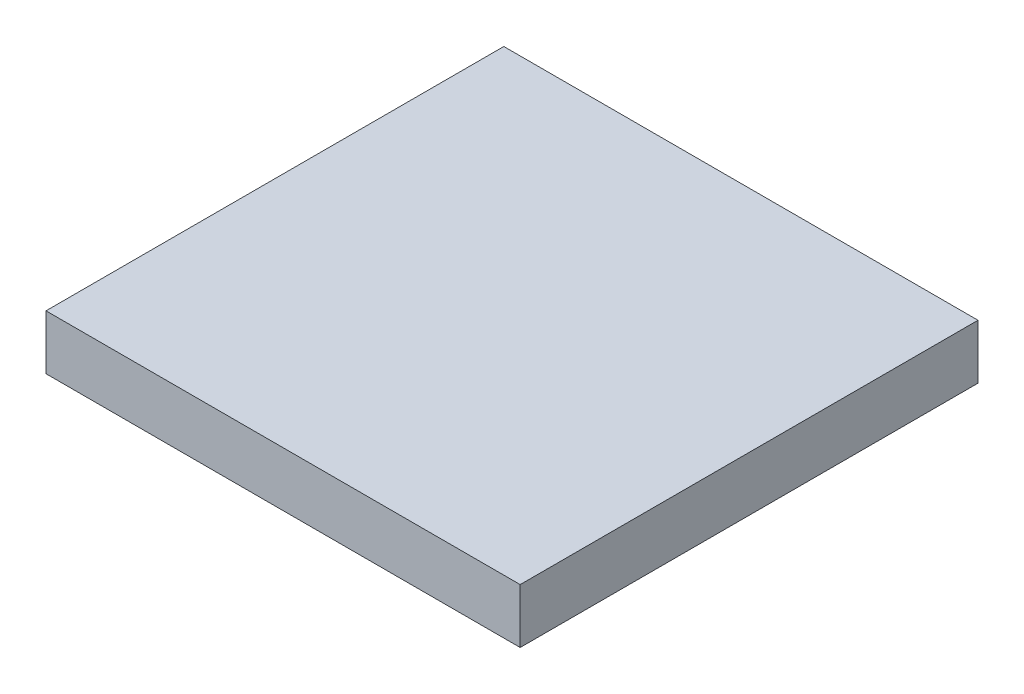
SolidWorks part; units mm, degrees
ref_plane "Front Plane" through (0, 0, 0) normal (0, 0, 1) x (1, 0, 0)
ref_plane "Top Plane" through (0, 0, 0) normal (0, 1, 0) x (1, 0, 0)
ref_plane "Right Plane" through (0, 0, 0) normal (1, 0, 0) x (0, 0, -1)
sketch "Sketch1" plane through (0, 0, 0) normal (0, 1, 0) x (1, 0, 0)
  line L1 (-43.5, 42) -> (43.5, 42)
  line L2 (-43.5, 42) -> (-43.5, -42)
  line L3 (-43.5, -42) -> (43.5, -42)
  line L4 (43.5, 42) -> (43.5, -42)
  line L5 (-43.5, 42) -> (43.5, -42) construction
  line L6 (-43.5, -42) -> (43.5, 42) construction
  point P0 (0, 0)
  dimension "D1" = 84
  dimension "D2" = 87
extrude "Boss-Extrude1" add sketch "Sketch1" along normal blind 10
